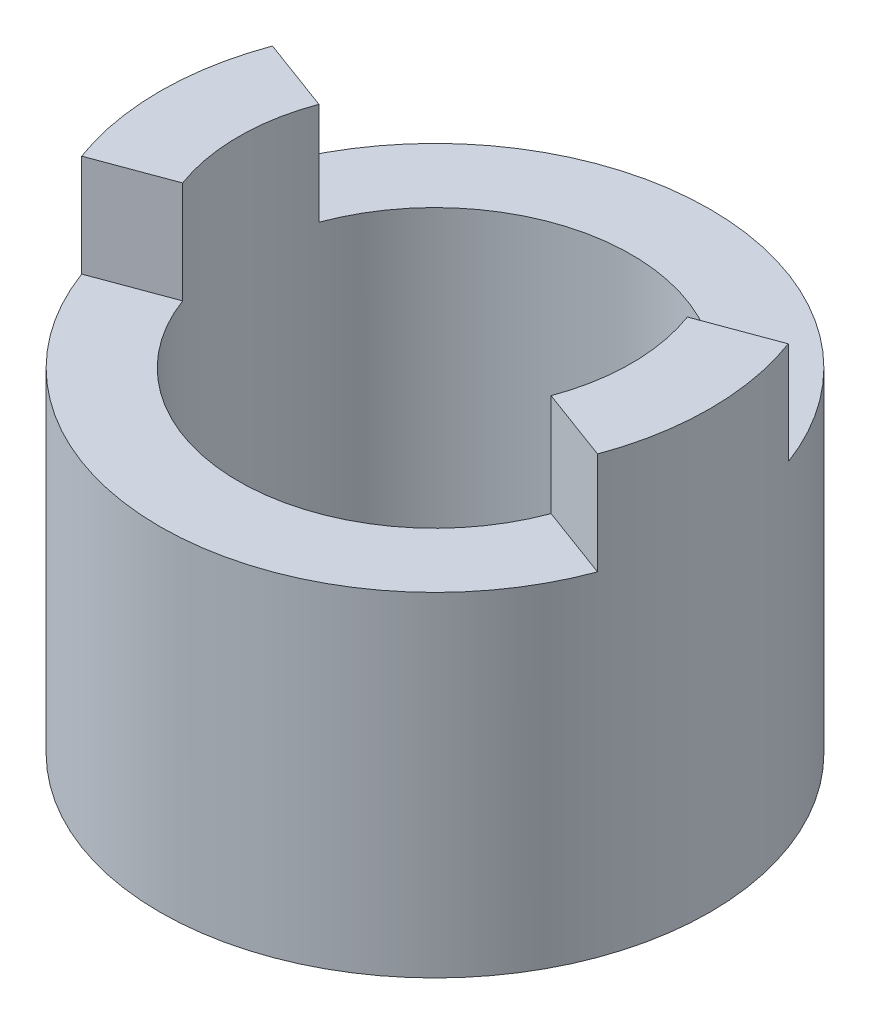
SolidWorks part; units mm, degrees
ref_plane "Front Plane" through (0, 0, 0) normal (0, 0, 1) x (1, 0, 0)
ref_plane "Top Plane" through (0, 0, 0) normal (0, 1, 0) x (1, 0, 0)
ref_plane "Right Plane" through (0, 0, 0) normal (1, 0, 0) x (0, 0, -1)
sketch "Sketch1" plane through (0, 0, 0) normal (0, 1, 0) x (1, 0, 0)
  circle A0 centre (0, 0) radius 2.5
  circle A1 centre (0, 0) radius 3.5
extrude "Boss-Extrude1" add sketch "Sketch1" along normal blind 4.25
sketch "Sketch2" plane through (0, 4.25, 0) normal (0, 1, 0) x (1, 0, 0)
  line L0 (2.3448, 0.8672) -> (3.2827, 1.2141)
  line L1 (0, 0) -> (3.5, 0) construction
  line L2 (2.3448, -0.8672) -> (3.2827, -1.2141)
  line L3 (0, 0) -> (0, 3.5) construction
  line L4 (-2.3448, -0.8672) -> (-3.2827, -1.2141)
  line L5 (-2.3448, 0.8672) -> (-3.2827, 1.2141)
  arc A0 (-3.2827, 1.2141) -> (-3.2827, -1.2141) centre (0, 0) ccw
  arc A1 (-2.3448, 0.8672) -> (-2.3448, -0.8672) centre (0, 0) ccw
  arc A2 (2.3448, -0.8672) -> (2.3448, 0.8672) centre (0, 0) ccw
  arc A3 (3.2827, -1.2141) -> (3.2827, 1.2141) centre (0, 0) ccw
extrude "Boss-Extrude2" add sketch "Sketch2" along normal blind 1.3
